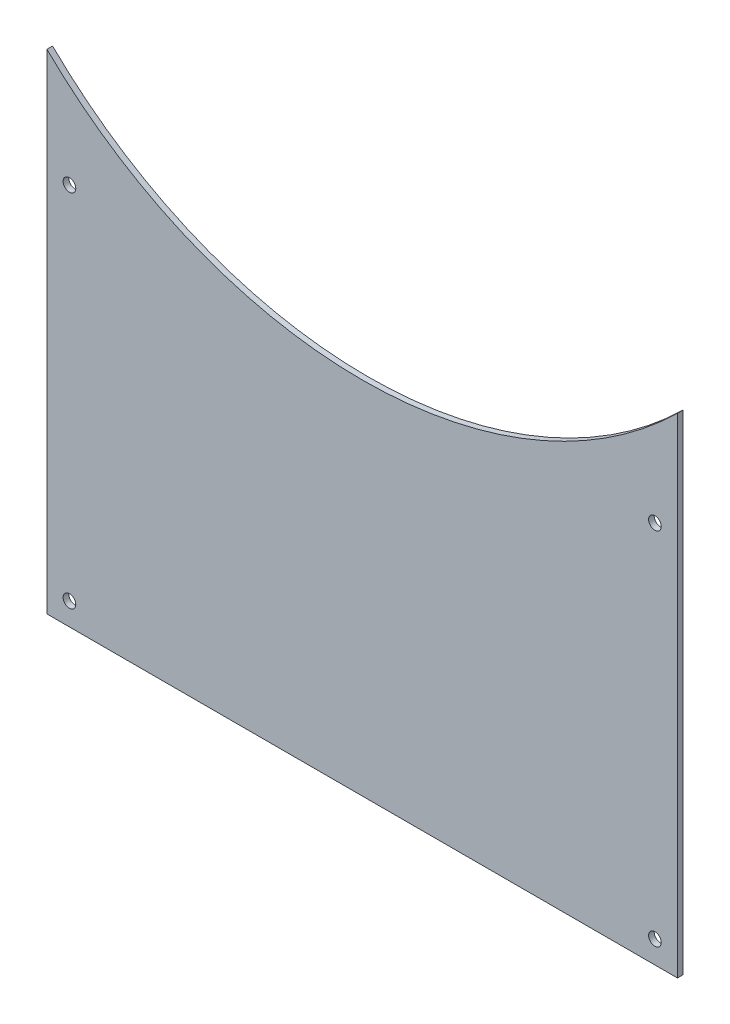
SolidWorks part; units mm, degrees
material "Acrylic (Medium-high impact)"
ref_plane "Front Plane" through (0, 0, 0) normal (0, 0, 1) x (1, 0, 0)
ref_plane "Top Plane" through (0, 0, 0) normal (0, 1, 0) x (1, 0, 0)
ref_plane "Right Plane" through (0, 0, 0) normal (1, 0, 0) x (0, 0, -1)
sketch "Sketch1" plane through (0, 0, 0) normal (0, 0, 1) x (1, 0, 0)
  line L1 (0, 0) -> (355.6, 0)
  line L2 (0, 0) -> (0, -279.4)
  line L3 (0, -279.4) -> (355.6, -279.4)
  line L4 (355.6, 0) -> (355.6, -279.4)
  dimension "D1" = 355.6
  dimension "D2" = 279.4
extrude "Boss-Extrude1" add sketch "Sketch1" along normal blind 3.175
sketch "Sketch2" plane through (0, 0, 3.175) normal (0, 0, 1) x (1, 0, 0)
  line L0 (177.8, 0) -> (177.8, -279.4) construction
  line L1 (355.6, 0) -> (0, 0) construction
  line L2 (0, -279.4) -> (355.6, -279.4) construction
  line L3 (0, -139.7) -> (355.6, -139.7) construction
  line L4 (0, 0) -> (0, -279.4) construction
  line L5 (355.6, -279.4) -> (355.6, 0) construction
  point P0 (12.7, -12.7)
  point P13 (342.9, -12.7)
  point P15 (342.9, -266.7)
  point P16 (12.7, -266.7)
  point P17 (12.7, -63.5)
  point P25 (342.9, -63.5)
  dimension "D1" = 12.7
  dimension "D2" = 12.7
  dimension "D3" = 203.2
hole_wizard "1/4 Clearance Hole1" positions "Sketch2" profile "Sketch3" hole size "1/4" standard "ANSI Inch"
sketch "Sketch3" plane through (342.9, -63.5, 3.175) normal (1, 0, 0) x (0, -1, 0)
  line L0 (0, 0) -> (0, 3.175)
  line L1 (0, 3.175) -> (3.5712, 3.175)
  line L2 (3.5712, 3.175) -> (3.5712, 0)
  line L5 (3.5712, 0) -> (0, 0)
  line L11 (0, -6.35) -> (0, 107.95) construction
  dimension "Thru Hole Dia." = 7.1425
  dimension "Thru Hole Depth" = 3.175
sketch "Sketch4" plane through (0, 0, 3.175) normal (0, 0, 1) x (1, 0, 0)
  line L0 (177.8, 84.9026) -> (177.8, -194.4974) construction
  line L5 (355.6, 0) -> (0, 0) construction
  line L6 (0, -279.4) -> (355.6, -279.4) construction
  circle A0 centre (177.8, 177.8) radius 254
  point P3 (177.8, 0)
  point P10 (177.8, 177.8)
  dimension "D2" = 508
  dimension "D1" = 457.2
extrude "Cut-Extrude1" cut sketch "Sketch4" against normal up to next
sketch "Sketch5" plane through (0, 0, 3.175) normal (0, 0, 1) x (1, 0, 0)
  line L0 (177.8, -279.4) -> (177.8, 177.8)
  line L3 (0, -3.5923) -> (0, -279.4)
  line L4 (0, -279.4) -> (355.6, -279.4)
  line L5 (355.6, -279.4) -> (355.6, -3.5923)
  line L6 (0, -3.5923) -> (0, -279.4)
  line L7 (0, -279.4) -> (355.6, -279.4)
  line L8 (355.6, -279.4) -> (355.6, -3.5923)
  arc A1 (0, -3.5923) -> (355.6, -3.5923) centre (177.8, 177.8) ccw
  arc A2 (0, -3.5923) -> (355.6, -3.5923) centre (177.8, 177.8) ccw
  dimension "D1" = 0
ref_point "Point1"
